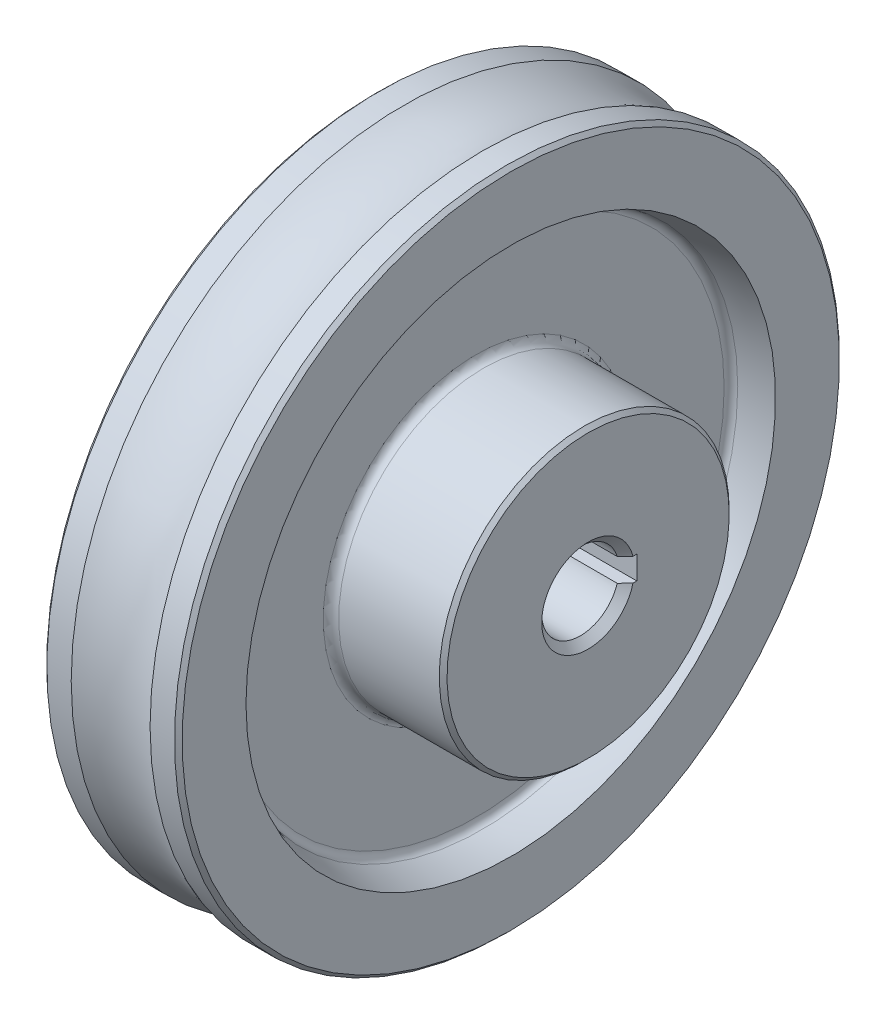
SolidWorks part; units mm, degrees
ref_plane "Alzado" through (0, 0, 0) normal (0, 0, 1) x (1, 0, 0)
ref_plane "Planta" through (0, 0, 0) normal (0, 1, 0) x (1, 0, 0)
ref_plane "Vista lateral" through (0, 0, 0) normal (1, 0, 0) x (0, 0, -1)
sketch "Croquis1" plane through (0, 0, 0) normal (0, 0, 1) x (1, 0, 0)
  line L0 (0, 0) -> (-17.5, 0) construction
  line L1 (-17.5, 0) -> (17.5, 0)
  line L2 (-17.5, 0) -> (-17.5, 86)
  line L3 (-17.5, 86) -> (17.5, 86)
  line L4 (17.5, 86) -> (17.5, 37.5)
  line L5 (17.5, 37.5) -> (37.5, 37.5)
  line L6 (37.5, 37.5) -> (37.5, 0)
  line L7 (37.5, 0) -> (17.5, 0)
  dimension "D1" = 17.5
  dimension "D2" = 20
  dimension "D3" = 86
  dimension "D4" = 55
  dimension "D5" = 37.5
revolve "Revolución1" add sketch "Croquis1" angle 360 about L0
sketch "Croquis2" plane through (0, 0, 0) normal (0, 0, 1) x (1, 0, 0)
  line L0 (0, 0) -> (-70.4514, 0) construction
  line L1 (0, 0) -> (0, 111) construction
  circle A0 centre (0, 111) radius 27
  point P3 (0, 84)
  dimension "D1" = 111
  dimension "D2" = 84
revolve "Cortar-Revolución1" cut sketch "Croquis2" angle 360 about L0
sketch "Croquis3" plane through (0, 0, 0) normal (0, 0, 1) x (1, 0, 0)
  line L0 (0, 0) -> (0, 111) construction
  line L1 (0, 0) -> (129.2288, 0) construction
  line L2 (-17.5, 86) -> (-17.5, -86) construction
  line L3 (-8.5, 37.5) -> (8.5, 37.5) construction
  line L4 (-8.5, 37.5) -> (-8.5, 65.8309)
  line L5 (-17.5, 68.5) -> (-17.5, 37.5)
  line L6 (-17.5, 37.5) -> (-8.5, 37.5)
  line L8 (8.5, 37.5) -> (8.5, 65.8309)
  line L9 (8.5, 37.5) -> (17.5, 37.5)
  line L10 (17.5, -37.5) -> (17.5, 37.5) construction
  line L11 (17.5, -86) -> (17.5, 86) construction
  line L12 (17.5, 37.5) -> (17.5, 68.5)
  circle A0 centre (0, 111) radius 31 construction
  arc A1 (-8.5, 65.8309) -> (-17.5, 68.5) centre (0, 111) cw
  arc A2 (17.5, 68.5) -> (8.5, 65.8309) centre (0, 111) cw
  point P3 (0, 80)
  dimension "D1" = 111
  dimension "D2" = 80
  dimension "D3" = 9
  dimension "D4" = 68.5
  dimension "D5" = 37.5
  dimension "D6" = 17
  dimension "D7" = 68.5
revolve "Cortar-Revolución2" cut sketch "Croquis3" angle 360 about L1
sketch "Croquis4" plane through (37.5, 0, 0) normal (1, 0, 0) x (0, 0, -1)
  circle A0 centre (0, 0) radius 10
  dimension "D1" = 20
extrude "Cortar-Extruir1" cut sketch "Croquis4" against normal through all
chamfer "Chaflán1" distance 1 angle 45 4 edges at (-17.5, 0, 37.5) (37.5, 37.5, 0) (17.5, 86, 0) (-17.5, 86, 0)
chamfer "Chaflán2" distance 2 angle 45 2 edges at (-17.5, 10, 0) (37.5, 10, 0)
fillet "Redondeo3" radius 2 2 edges at (8.5, 0, 65.8309) (-8.5, 0, 65.8309)
fillet "Redondeo5" radius 2 2 edges at (8.5, 0, 37.5) (-8.5, 0, 37.5)
sketch "Croquis5" plane through (0, 0, 0) normal (1, 0, 0) x (0, 0, -1)
  line L0 (0, 0) -> (28.4959, 0) construction
  line L1 (12.6, 0) -> (12.6, 3)
  line L2 (12.6, 0) -> (12.6, -3)
  line L3 (12.6, -3) -> (9.5394, -3)
  line L4 (12.6, 3) -> (9.5394, 3)
  circle A0 centre (0, 0) radius 10 construction
  arc A1 (9.5394, -3) -> (9.5394, 3) centre (0, 0) ccw
  point P10 (0, 0)
  point P12 (11.0697, 3)
  point P13 (0, 0)
  dimension "D1" = 12.6
  dimension "D2" = 6
extrude "Cortar-Extruir2" cut sketch "Croquis5" against normal up to surface and the other way up to surface up to face at (-17.5, -12, 0) other way up to face at (37.5, 12, 0)
